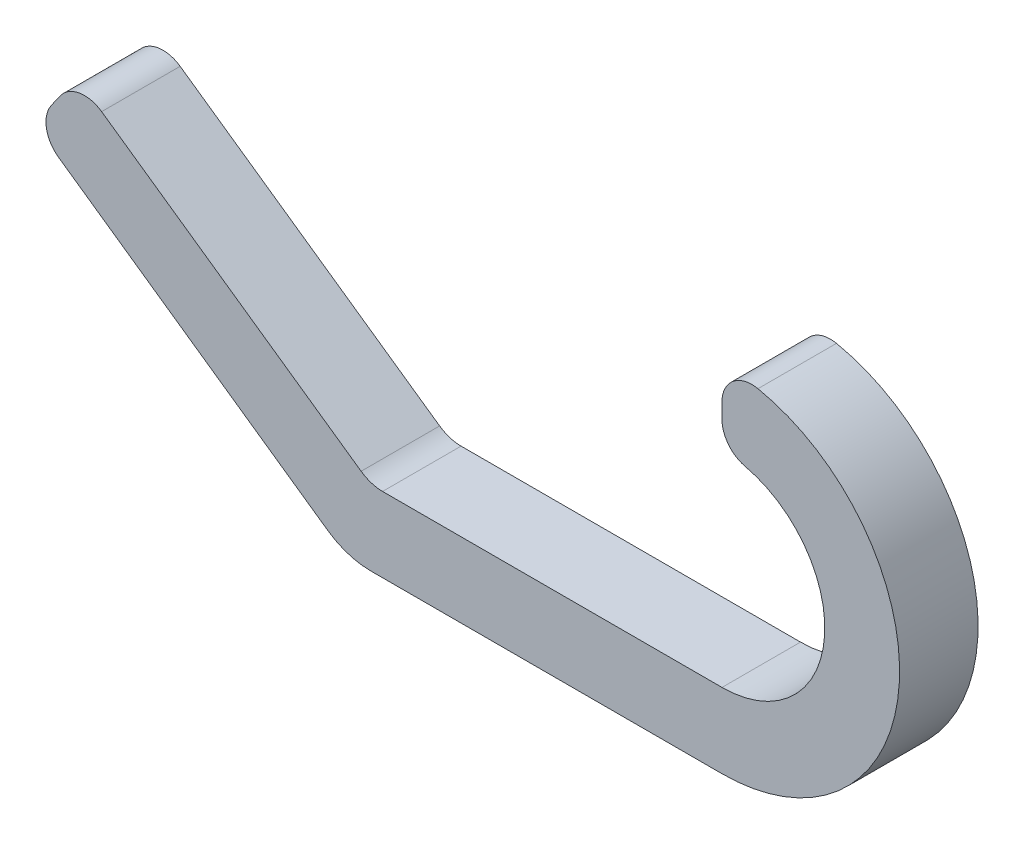
SolidWorks part; units mm, degrees
ref_plane "Plan de face" through (0, 0, 0) normal (0, 0, 1) x (1, 0, 0)
ref_plane "Plan de dessus" through (0, 0, 0) normal (0, 1, 0) x (1, 0, 0)
ref_plane "Plan de droite" through (0, 0, 0) normal (1, 0, 0) x (0, 0, -1)
sketch "Esquisse1" plane through (0, 0, 0) normal (0, 0, 1) x (1, 0, 0)
  line L0 (0, 0) -> (93.9519, 0)
  line L1 (0, 0) -> (-78.5481, 55)
  line L2 (-78.5481, 55) -> (-78.5481, 0) construction
  line L3 (121.4519, 27.5) -> (121.4519, 65.2066) construction
  line L4 (93.9519, 0) -> (93.9519, 55) construction
  line L5 (-78.5481, 55) -> (93.9519, 55) construction
  line L6 (-78.5481, 0) -> (0, 0) construction
  arc A0 (93.9519, 0) -> (93.9519, 55) centre (93.9519, 27.5) ccw
  dimension "D1" = 145
  dimension "D2" = 200
  dimension "D3" = 55
sketch "Esquisse2" plane through (0, 0, 0) normal (0, 0, 1) x (1, 0, 0)
  line L0 (0, 0) -> (93.9519, 0) construction
  line L1 (0, 0) -> (-78.5481, 55) construction
  line L2 (0, 0) -> (93.9519, 0)
  line L3 (0, 0) -> (-78.5481, 55)
  line L4 (-6.306, -20) -> (93.9519, -20)
  line L5 (-6.306, -20) -> (-90.0197, 38.617)
  line L6 (-90.0197, 38.617) -> (-78.5481, 55)
  line L7 (93.9519, 75) -> (93.9519, 55)
  arc A0 (93.9519, 0) -> (93.9519, 55) centre (93.9519, 27.5) ccw construction
  arc A1 (93.9519, 0) -> (93.9519, 55) centre (93.9519, 27.5) ccw
  arc A2 (93.9519, -20) -> (93.9519, 75) centre (93.9519, 27.5) ccw
  dimension "D1" = 20
extrude "Boss.-Extru.1" add sketch "Esquisse2" along normal blind 21
fillet "Congé1" radius 8 4 edges at (93.9519, 55, 10.5) (93.9519, 75, 10.5) (-90.0197, 38.617, 10.5) (-78.5481, 55, 10.5)
fillet "Congé2" radius 20 1 edges at (-6.306, -20, 10.5)
fillet "Congé3" radius 10 1 edges at (0, 0, 10.5)
